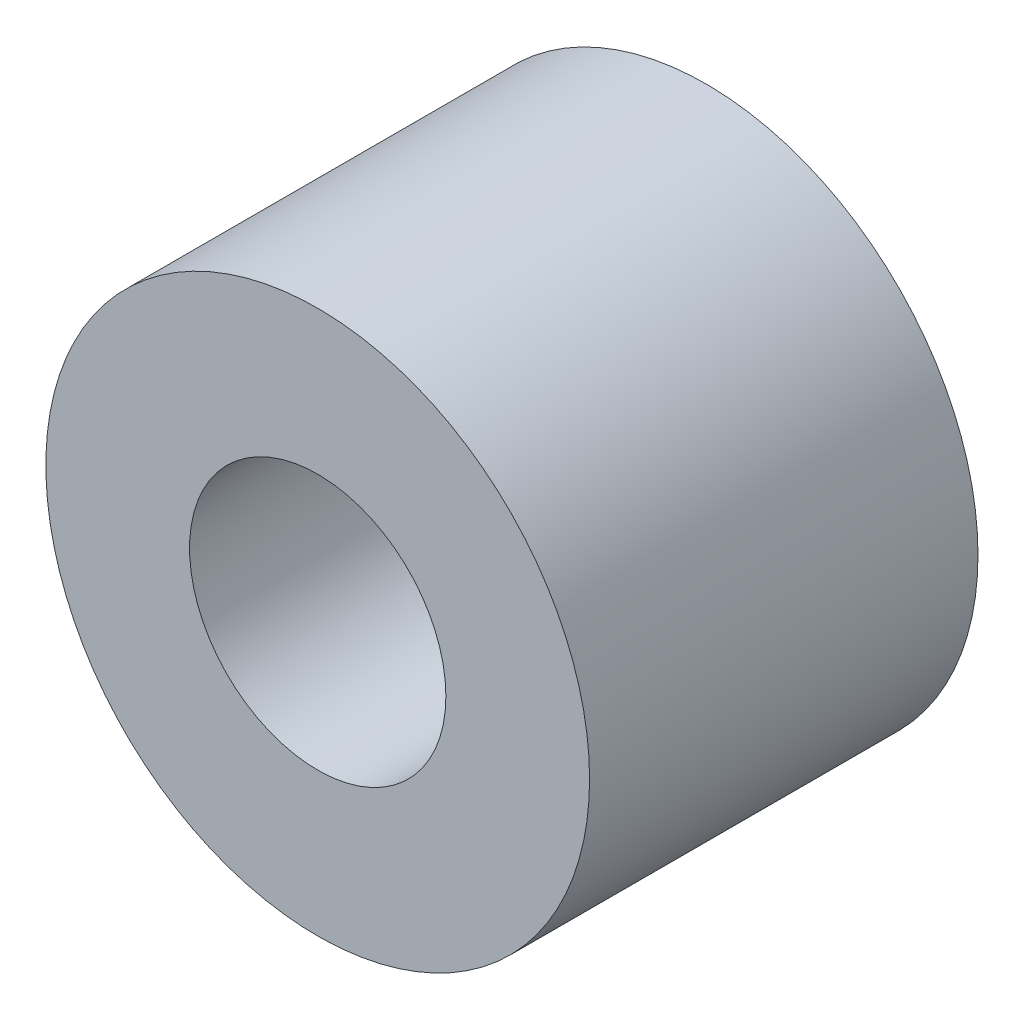
SolidWorks part; units mm, degrees
material "ABS"
ref_plane "前视基准面" through (0, 0, 0) normal (0, 0, 1) x (1, 0, 0)
ref_plane "上视基准面" through (0, 0, 0) normal (0, 1, 0) x (1, 0, 0)
ref_plane "右视基准面" through (0, 0, 0) normal (1, 0, 0) x (0, 0, -1)
other "Configuration Table"
sketch "草图1" plane through (0, 0, 0) normal (0, 0, 1) x (1, 0, 0)
  circle A0 centre (0, 0) radius 1.65
  circle A1 centre (0, 0) radius 3.5
  dimension "D1" = 3.3
  dimension "D2" = 7
extrude "凸台-拉伸1" add sketch "草图1" along normal blind 5
